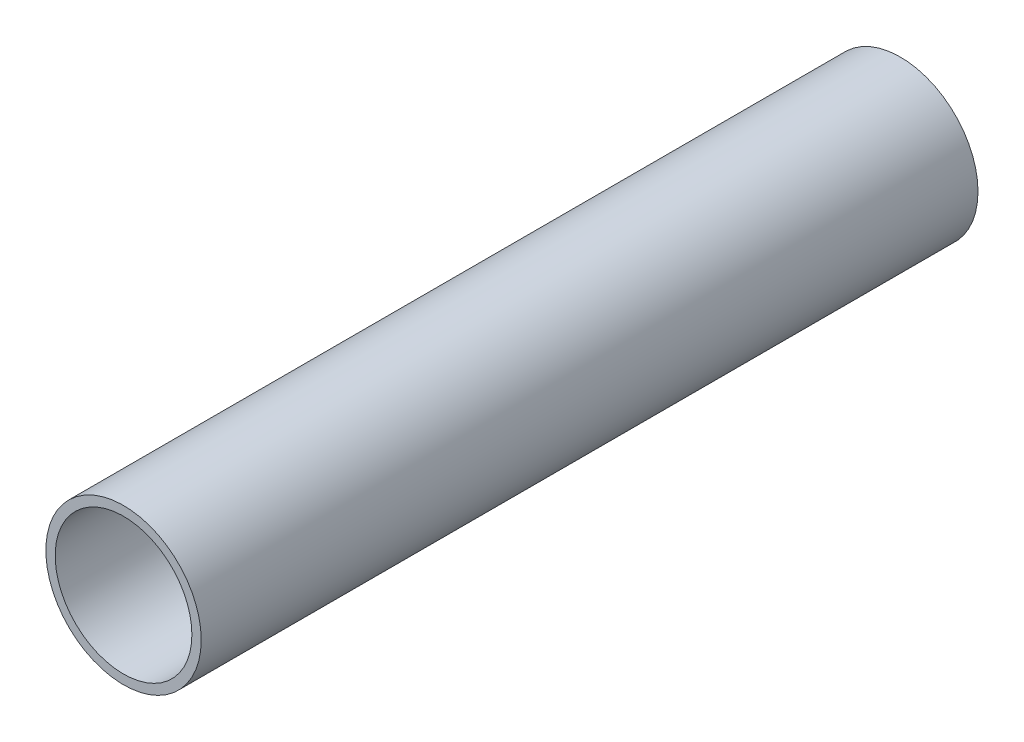
SolidWorks part; units mm, degrees
ref_plane "Front Plane" through (0, 0, 0) normal (0, 0, 1) x (1, 0, 0)
ref_plane "Top Plane" through (0, 0, 0) normal (0, 1, 0) x (1, 0, 0)
ref_plane "Right Plane" through (0, 0, 0) normal (1, 0, 0) x (0, 0, -1)
sketch "Sketch1" plane through (0, 0, 0) normal (0, 0, 1) x (1, 0, 0)
  circle A0 centre (0, 0) radius 2.5
  circle A1 centre (0, 0) radius 2.2
  dimension "D1" = 4.4
  dimension "D2" = 5
extrude "Boss-Extrude1" add sketch "Sketch1" along normal blind 25
